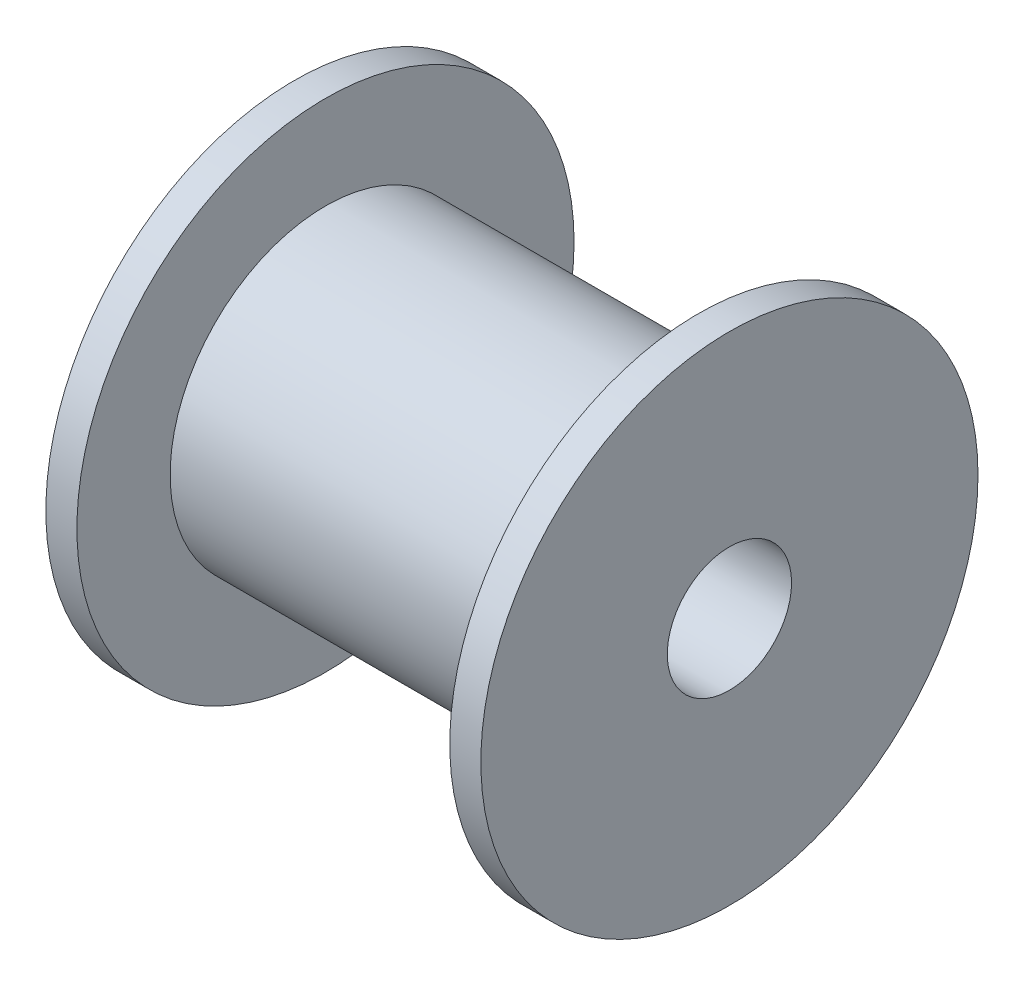
SolidWorks part; units mm, degrees
ref_plane "Front Plane" through (0, 0, 0) normal (0, 0, 1) x (1, 0, 0)
ref_plane "Top Plane" through (0, 0, 0) normal (0, 1, 0) x (1, 0, 0)
ref_plane "Right Plane" through (0, 0, 0) normal (1, 0, 0) x (0, 0, -1)
sketch "Sketch1" plane through (0, 0, 0) normal (1, 0, 0) x (0, 0, -1)
  circle A0 centre (0, 0) radius 12.5
  circle A1 centre (0, 0) radius 5
  dimension "D1" = 10
  dimension "D2" = 25
extrude "Boss-Extrude1" add sketch "Sketch1" along normal mid plane 30
sketch "Sketch2" plane through (15, 0, 0) normal (1, 0, 0) x (0, 0, -1)
  circle A0 centre (0, 0) radius 20
  dimension "D1" = 40
extrude "Boss-Extrude2" add sketch "Sketch2" along normal blind 2.5
mirror "Mirror1" about plane through (0, 0, 0) normal (1, 0, 0) of "Boss-Extrude2"
sketch "Sketch3" plane through (17.5, 0, 0) normal (1, 0, 0) x (0, 0, -1)
  circle A0 centre (0, 0) radius 5
  dimension "D1" = 10
extrude "Cut-Extrude1" cut sketch "Sketch3" against normal through all both and the other way through all
